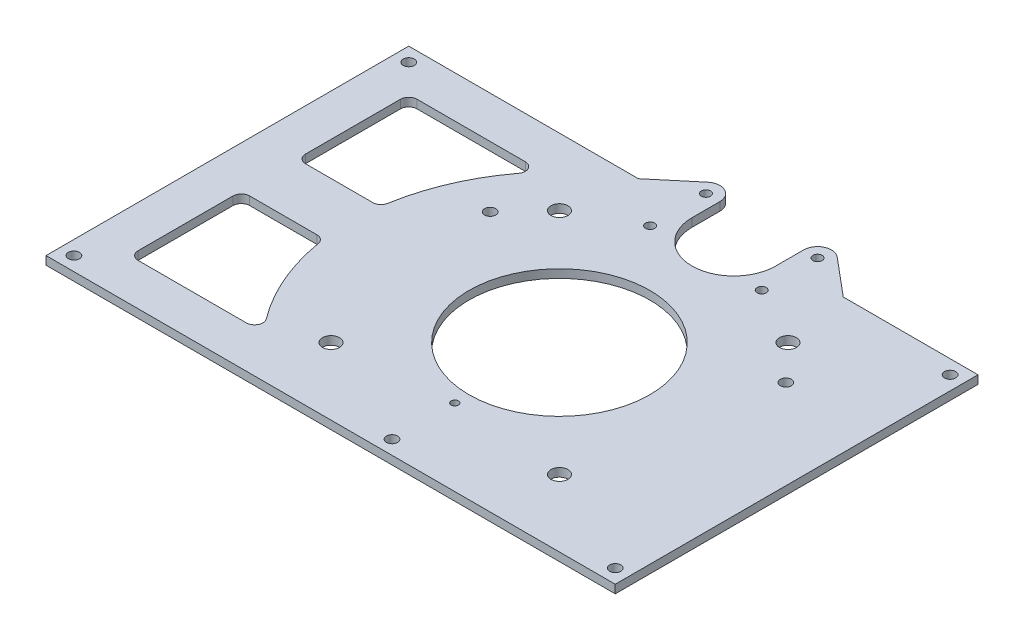
SolidWorks part; units mm, degrees
material "5052-H34"
ref_plane "正面" through (0, 0, 0) normal (0, 0, 1) x (1, 0, 0)
ref_plane "平面" through (0, 0, 0) normal (0, 1, 0) x (1, 0, 0)
ref_plane "右側面" through (0, 0, 0) normal (1, 0, 0) x (0, 0, -1)
sketch "ｽｹｯﾁ1" plane through (0, 0, 0) normal (0, 1, 0) x (1, 0, 0)
  line L0 (119, 0) -> (119, 65) construction
  line L1 (0, 0) -> (204, 0)
  line L2 (0, 0) -> (0, 130)
  line L3 (0, 130) -> (82.2832, 130)
  line L4 (204, 0) -> (204, 130)
  line L5 (159.9415, 24.0585) -> (119, 65) construction
  line L6 (119, 65) -> (119, 5) construction
  line L7 (119, 65) -> (66.0231, 93.1683) construction
  line L8 (119, 65) -> (119, 127.5) construction
  line L9 (119, 127.5) -> (139, 127.5) construction
  line L10 (99, 137.5) -> (139, 137.5) construction
  line L11 (99, 137.5) -> (99, 117.5) construction
  line L12 (99, 117.5) -> (139, 117.5) construction
  line L13 (139, 137.5) -> (139, 117.5) construction
  line L14 (99, 137.5) -> (139, 117.5) construction
  line L15 (99, 117.5) -> (139, 137.5) construction
  line L16 (119, 65) -> (204, 65) construction
  line L17 (134, 137.5) -> (134, 130)
  line L18 (104, 137.5) -> (104, 130)
  line L19 (142.2139, 141.3302) -> (155.7168, 130)
  line L20 (95.7861, 141.3302) -> (82.2832, 130)
  line L21 (82.2832, 130) -> (99, 130) construction
  line L22 (99, 130) -> (104.2098, 130)
  line L23 (104, 137.5) -> (104, 127.5)
  line L24 (134, 137.5) -> (134, 127.5)
  line L25 (106.7526, 130) -> (114, 130) construction
  line L26 (133.7902, 130) -> (204, 130)
  line L27 (104.2098, 130) -> (106.7526, 130) construction
  line L28 (114, 130) -> (124, 130) construction
  line L29 (124, 130) -> (131.2474, 130) construction
  line L30 (131.2474, 130) -> (133.7902, 130) construction
  line L31 (119, 0) -> (119, 130) construction
  circle A0 centre (119, 65) radius 32.4
  circle A1 centre (119, 65) radius 47.5 construction
  circle A2 centre (159.9415, 24.0585) radius 10.5 construction
  circle A3 centre (159.9415, 24.0585) radius 3.05
  circle A4 centre (78.0585, 24.0585) radius 3.05
  circle A5 centre (78.0585, 24.0585) radius 10.5 construction
  circle A6 centre (78.0585, 105.9415) radius 3.05
  circle A7 centre (78.0585, 105.9415) radius 10.5 construction
  circle A8 centre (159.9415, 105.9415) radius 3.05
  circle A9 centre (159.9415, 105.9415) radius 10.5 construction
  circle A10 centre (119, 65) radius 60 construction
  circle A13 centre (119, 5) radius 2
  circle A16 centre (66.0231, 93.1683) radius 2
  circle A17 centre (171.9769, 93.1683) radius 2
  circle A18 centre (78.0585, 105.9415) radius 12 construction
  circle A19 centre (66.0231, 93.1683) radius 4 construction
  circle A20 centre (119, 27.5) radius 1.3
  circle A21 centre (119, 127.5) radius 12.5 construction
  arc A22 (104.2098, 130) -> (133.7902, 130) centre (119, 127.5) ccw
  circle A23 centre (119, 127.5) radius 21 construction
  circle A24 centre (139, 137.5) radius 1.65
  circle A25 centre (139, 117.5) radius 1.65
  circle A26 centre (99, 117.5) radius 1.65
  circle A27 centre (99, 137.5) radius 1.65
  circle A28 centre (199, 125) radius 2
  circle A29 centre (199, 5) radius 2
  circle A30 centre (5, 125) radius 2
  circle A31 centre (5, 5) radius 2
  circle A32 centre (139, 137.5) radius 5
  circle A33 centre (99, 137.5) radius 5
  arc A34 (130.1803, 137.5) -> (107.8197, 137.5) centre (119, 127.5) ccw construction
  arc A35 (107.8197, 137.5) -> (105.5836, 134.2082) centre (119, 127.5) ccw construction
  arc A36 (105.5836, 134.2082) -> (104.2098, 130) centre (119, 127.5) ccw construction
  arc A37 (132.4164, 134.2082) -> (130.1803, 137.5) centre (119, 127.5) ccw construction
  arc A38 (133.7902, 130) -> (132.4164, 134.2082) centre (119, 127.5) ccw construction
  point P23 (119, 65)
  point P31 (119, 65)
  point P33 (119, 65)
  point P71 (102, 0)
  dimension "D3" = 64.8
  dimension "D5" = 95
  dimension "D6" = 21
  dimension "D7" = 6.1
  dimension "D11" = 120
  dimension "D12" = 4
  dimension "D16" = 24
  dimension "D17" = 8
  dimension "D18" = 25
  dimension "D22" = 42
  dimension "D24" = 3.3
  dimension "D25" = 4
  dimension "D28" = 2.6
  dimension "D29" = 10
  dimension "D20" = 30
  dimension "D1" = 204
  dimension "D2" = 130
  dimension "D8" = 45
  dimension "D10" = 57.9
  dimension "D14" = 118
  dimension "D4" = 65
  dimension "D15" = 37.5
  dimension "D19" = 62.5
  dimension "D21" = 40
  dimension "D23" = 20
  dimension "D26" = 5
  dimension "D27" = 5
  dimension "D30" = 40
  dimension "D32" = 5
  dimension "D31" = 17
  dimension "D9" = 4
  dimension "D13" = 2
extrude "ﾎﾞｽ - 押し出し1" add sketch "ｽｹｯﾁ1" along normal blind 3 contours A32 A24 | A33 A27 | L22 A32 | L18 A33 L20 L3 L2 L1 L4 L22 A32 L17 A22 A30 A26 A17 A16 A13 A8 A6 A4 A3 A0 A20 A25 A28 A29 A31 | A32 L22 L19
sketch "ｽｹｯﾁ2" plane through (0, 3, 0) normal (0, 1, 0) x (1, 0, 0)
  line L0 (63.0983, 115) -> (15, 115)
  line L1 (15, 115) -> (15, 15)
  line L2 (15, 15) -> (63.0983, 15)
  line L4 (0, 0) -> (0, 130) construction
  line L5 (44.6697, 75) -> (15, 75)
  line L6 (0, 65) -> (-50000, 65) construction
  line L7 (44.6697, 55) -> (15, 55)
  line L8 (0, 130) -> (82.2832, 130) construction
  line L10 (0, 0) -> (204, 0) construction
  circle A0 centre (119, 65) radius 75
  point P3 (64.3352, 116.3494)
  point P20 (0, 65)
  point P24 (59.7592, 19.0052)
  point P26 (52.1218, 92.1515)
  dimension "D1" = 150
  dimension "D2" = 15
  dimension "D3" = 15
  dimension "D4" = 20
  dimension "D5" = 15
extrude "ｶｯﾄ - 押し出し1" cut sketch "ｽｹｯﾁ2" against normal through all contours A0 L0 L1 L5 | A0 L7 L1 L2
fillet "ﾌｨﾚｯﾄ1" radius 3 8 edges at (63.0983, 1.5, -15) (15, 1.5, -15) (15, 1.5, -55) (44.6697, 1.5, -55) (44.6697, 1.5, -75) (15, 1.5, -75) (15, 1.5, -115) (63.0983, 1.5, -115)
equation "\"D10@ｽｹｯﾁ1\"=\"D5@ｽｹｯﾁ1\"/2+\"D6@ｽｹｯﾁ1\"/2-0.1"
equation "\"D19@ｽｹｯﾁ1\"=\"D18@ｽｹｯﾁ1\"/2+100/2"
